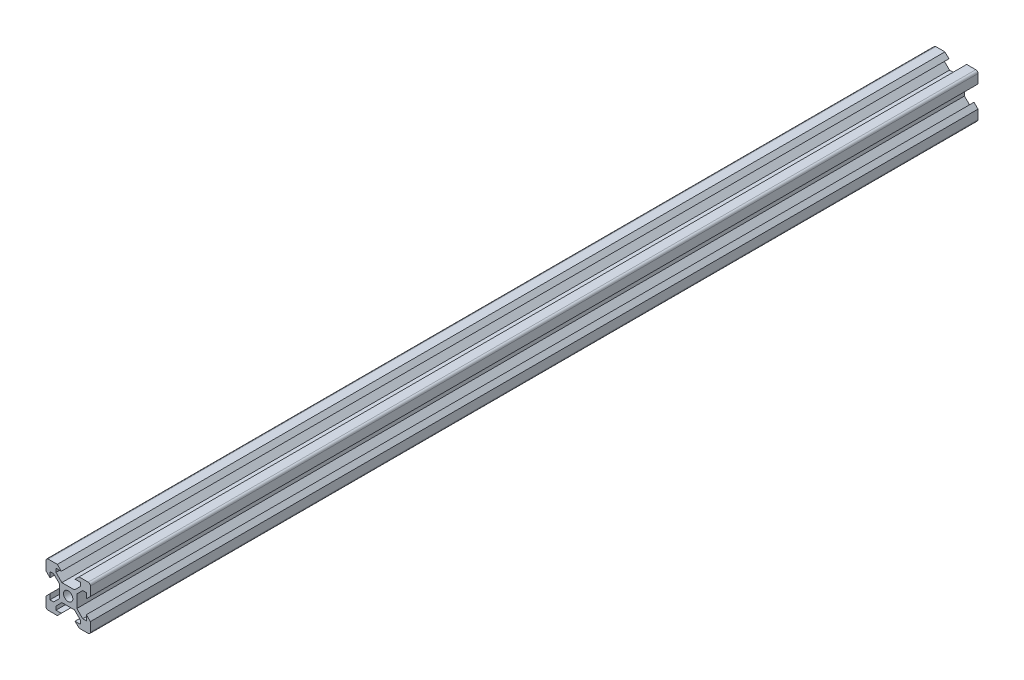
SolidWorks part; units mm, degrees
ref_plane "Front (XY)" through (0, 0, 0) normal (0, 0, 1) x (1, 0, 0)
ref_plane "Top (XZ)" through (0, 0, 0) normal (0, 1, 0) x (1, 0, 0)
ref_plane "Right (YZ)" through (0, 0, 0) normal (1, 0, 0) x (0, 0, -1)
sketch "Sketch2" plane through (0, 0, 0) normal (0, 0, 1) x (1, 0, 0)
  line L0 (-10, 10) -> (10, 10)
  line L1 (10, 10) -> (10, -10)
  line L2 (10, -10) -> (-10, -10)
  line L3 (-10, -10) -> (-10, 10)
  point P4 (0, -10)
  point P6 (10, 0)
  dimension "D1" = 20
  dimension "D2" = 20
extrude "Boss-Extrude1" add sketch "Sketch2" against normal blind 400
sketch "Sketch3" plane through (0, 0, 0) normal (0, 0, 1) x (1, 0, 0)
  line L0 (0, 0) -> (0, 10) construction
  line L1 (0, 10) -> (-3.1, 10) construction
  line L2 (10, 10) -> (-10, 10) construction
  line L3 (-3.1, 10) -> (-3.1, 8.2) construction
  line L4 (3.1, 10) -> (3.1, 8.2) construction
  line L5 (-3.1, 8.2) -> (-4.9, 10)
  line L6 (3.1, 8.2) -> (4.9, 10)
  line L7 (-3.1, 8.2) -> (-5.5, 8.2)
  line L8 (3.1, 8.2) -> (5.5, 8.2)
  line L9 (-5.5, 8.2) -> (-5.5, 6.56)
  line L10 (5.5, 8.2) -> (5.5, 6.56)
  line L11 (0, 10) -> (0, 3.9) construction
  line L12 (2.84, 3.9) -> (-2.84, 3.9)
  line L13 (-2.84, 3.9) -> (-5.5, 6.56)
  line L14 (2.84, 3.9) -> (5.5, 6.56)
  line L15 (-4.9, 10) -> (4.9, 10)
  point P21 (0, 3.9)
  dimension "D1" = 3.1
  dimension "D2" = 1.8
  dimension "D3" = 90
  dimension "D4" = 2.4
  dimension "D5" = 1.64
  dimension "D6" = 6.1
  dimension "D7" = 5.68
extrude "Cut-Extrude1" cut sketch "Sketch3" along normal through all and the other way through all
sketch "Sketch8" plane through (0, 0, 0) normal (1, 0, 0) x (0, 0, -1)
  line L0 (0, 0) -> (-11.2124, 0) construction
  line L1 (0, -10) -> (0, 10) construction
pattern_circular "CirPattern2" count 4 over 360 about axis through (0, 0, 0) along (0, 0, 1) of "Cut-Extrude1"
sketch "Sketch9" plane through (0, 0, 0) normal (0, 0, 1) x (1, 0, 0)
  circle A0 centre (0, 0) radius 2.1
  dimension "D1" = 4.2
extrude "Cut-Extrude2" cut sketch "Sketch9" against normal through all
fillet "Fillet1" radius 1 4 edges at (10, -10, -200) (-10, -10, -200) (-10, 10, -200) (10, 10, -200)
